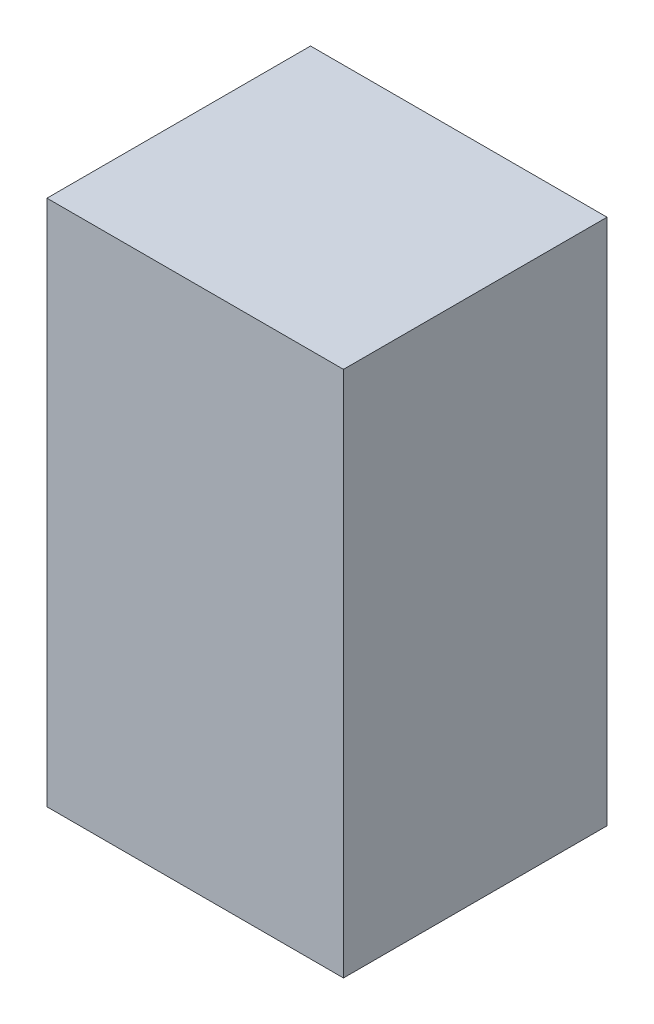
SolidWorks part; units mm, degrees
ref_plane "Front Plane" through (0, 0, 0) normal (0, 0, 1) x (1, 0, 0)
ref_plane "Top Plane" through (0, 0, 0) normal (0, 1, 0) x (1, 0, 0)
ref_plane "Right Plane" through (0, 0, 0) normal (1, 0, 0) x (0, 0, -1)
other "Configuration Table"
sketch "Sketch1" plane through (0, 0, 0) normal (0, 0, 1) x (1, 0, 0)
  line L1 (520, 220) -> (565, 220)
  line L2 (520, 220) -> (520, 300)
  line L3 (520, 300) -> (565, 300)
  line L4 (565, 220) -> (565, 300)
extrude "OVEN_pano_SSR_1_1" add sketch "Sketch1" against normal blind 40 from offset 208 separate body
